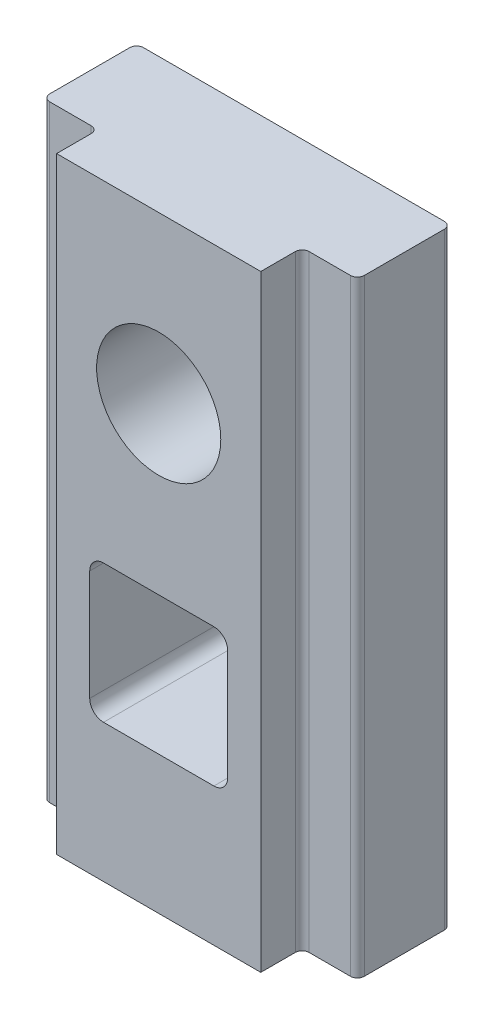
SolidWorks part; units mm, degrees
material "ABS"
ref_plane "Front Plane" through (0, 0, 0) normal (0, 0, 1) x (1, 0, 0)
ref_plane "Top Plane" through (0, 0, 0) normal (0, 1, 0) x (1, 0, 0)
ref_plane "Right Plane" through (0, 0, 0) normal (1, 0, 0) x (0, 0, -1)
sketch "Sketch1" plane through (0, 0, 0) normal (0, 1, 0) x (1, 0, 0)
  line L0 (0, 4) -> (0, -3.5298) construction
  line L1 (6, 4) -> (-6, 4) construction
  line L2 (-6, 4) -> (-6, 0) construction
  line L3 (-6, 0) -> (-4, 0) construction
  line L4 (-4, 0) -> (-4, -1.5) construction
  line L5 (-4, -1.5) -> (4, -1.5) construction
  line L6 (4, 0) -> (4, -1.5) construction
  line L7 (6, 0) -> (4, 0) construction
  line L8 (6, 4) -> (6, 0) construction
  line L9 (3.7, 0.3) -> (3.7, -1.2)
  line L10 (-3.7, -1.2) -> (3.7, -1.2)
  line L11 (-3.7, 0.3) -> (-3.7, -1.2)
  line L12 (-5.7, 0.3) -> (-3.7, 0.3)
  line L13 (-5.7, 3.7) -> (-5.7, 0.3)
  line L14 (5.7, 3.7) -> (-5.7, 3.7)
  line L15 (5.7, 3.7) -> (5.7, 0.3)
  line L16 (5.7, 0.3) -> (3.7, 0.3)
  point P10 (0, -1.5)
  dimension "D1" = 6
  dimension "D2" = 4
  dimension "D3" = 1.5
  dimension "D4" = 4
  dimension "D5" = 0.3
extrude "Boss-Extrude1" add sketch "Sketch1" against normal blind 22
sketch "Sketch2" plane through (0, 0, 1.2) normal (0, 0, 1) x (1, 0, 0)
  line L0 (0, 0) -> (0, -22) construction
  line L1 (-3.7, 0) -> (3.7, 0) construction
  line L2 (-3.7, -22) -> (3.7, -22) construction
  line L4 (-2.5, -12) -> (2.5, -12)
  line L5 (-2.5, -12) -> (-2.5, -17)
  line L6 (-2.5, -17) -> (2.5, -17)
  line L7 (2.5, -12) -> (2.5, -17)
  line L8 (-2.5, -12) -> (2.5, -17) construction
  line L9 (-2.5, -17) -> (2.5, -12) construction
  circle A0 centre (0, -6) radius 2.25
  circle A1 centre (0, -6) radius 4 construction
  point P9 (0, -14.5)
  point P13 (0, -10)
  dimension "D1" = 4.5
  dimension "D2" = 8
  dimension "D4" = 5
  dimension "D5" = 2
  dimension "D3" = 6
extrude "Cut-Extrude1" cut sketch "Sketch2" against normal through all
fillet "Fillet1" radius 0.25 6 edges at (5.7, -11, -3.7) (5.7, -11, -0.3) (3.7, -11, -0.3) (-3.7, -11, -0.3) (-5.7, -11, -0.3) (-5.7, -11, -3.7)
fillet "Fillet2" radius 0.5 4 edges at (2.5, -17, -1.25) (-2.5, -17, -1.25) (-2.5, -12, -1.25) (2.5, -12, -1.25)
